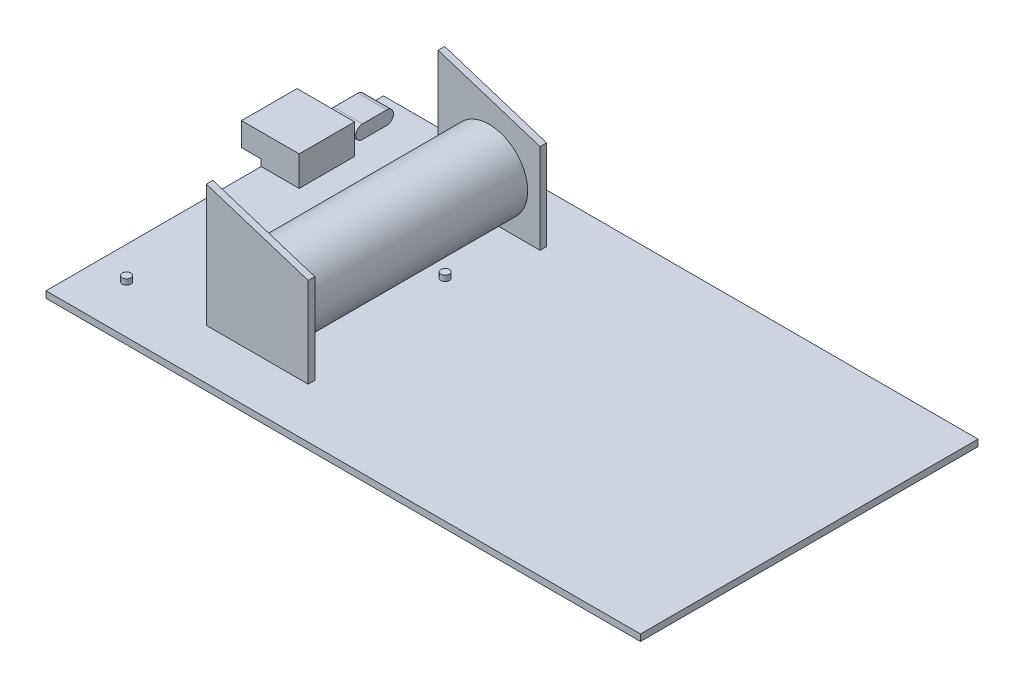
SolidWorks part; units mm, degrees
ref_plane "Front Plane" through (0, 0, 0) normal (0, 0, 1) x (1, 0, 0)
ref_plane "Top Plane" through (0, 0, 0) normal (0, 1, 0) x (1, 0, 0)
ref_plane "Right Plane" through (0, 0, 0) normal (1, 0, 0) x (0, 0, -1)
sketch "Sketch1" plane through (0, 0, 0) normal (0, 1, 0) x (1, 0, 0)
  line L1 (-70.45, -40) -> (70.45, -40)
  line L2 (-70.45, -40) -> (-70.45, 40)
  line L3 (-70.45, 40) -> (70.45, 40)
  line L4 (70.45, -40) -> (70.45, 40)
  line L5 (-70.45, -40) -> (70.45, 40) construction
  line L6 (-70.45, 40) -> (70.45, -40) construction
  point P0 (0, 0)
  dimension "D1" = 140.9
  dimension "D2" = 80
extrude "PCB" add sketch "Sketch1" along normal blind 1.55
sketch "Sketch2" plane through (-70.45, 0, 0) normal (-1, 0, 0) x (0, 0, 1)
  line L0 (-31.43, 1.55) -> (-31.43, 3.15)
  line L1 (-40, 1.55) -> (40, 1.55) construction
  line L2 (-40, 1.55) -> (-40, 0) construction
  dimension "D1" = 1.6
  dimension "D2" = 8.57
sketch "Sketch3" plane through (-70.45, 0, 0) normal (-1, 0, 0) x (0, 0, 1)
  line L0 (-34.3, 3.15) -> (-28.56, 3.15) construction
  line L1 (-34.3, 4.75) -> (-28.56, 4.75)
  line L2 (-34.3, 1.55) -> (-28.56, 1.55)
  arc A0 (-34.3, 4.75) -> (-34.3, 1.55) centre (-34.3, 3.15) ccw
  arc A1 (-28.56, 1.55) -> (-28.56, 4.75) centre (-28.56, 3.15) ccw
  point P2 (-31.43, 3.15)
  dimension "D1" = 5.74
extrude "bodyC" add sketch "Sketch3" against normal blind 6.45 and the other way blind 0.4
sketch "Sketch4" plane through (0, 1.55, 0) normal (0, 1, 0) x (1, 0, 0)
  line L0 (70.45, 40) -> (-70.45, 40) construction
  line L1 (-61.45, 11) -> (-75.1, 11)
  line L2 (-61.45, 11) -> (-61.45, 24.15)
  line L3 (-61.45, 24.15) -> (-75.1, 24.15)
  line L4 (-75.1, 11) -> (-75.1, 24.15)
  line L6 (-70.45, 28.56) -> (-70.45, -40) construction
  dimension "D1" = 13.65
  dimension "D2" = 13.15
  dimension "D3" = 15.85
  dimension "D4" = 4.65
extrude "Boss-Extrude4" add sketch "Sketch4" along normal blind 7.1 and the other way blind 1.55
sketch "Sketch5" plane through (0, 0, -11) normal (0, 0, 1) x (1, 0, 0)
  line L0 (-75.1, 0) -> (-75.1, 8.65) construction
  line L1 (-70.45, 0) -> (-75.1, 0)
  line L2 (-70.45, 0) -> (-70.45, 3.1)
  line L3 (-70.45, 3.1) -> (-75.1, 3.1)
  line L4 (-75.1, 0) -> (-75.1, 3.1)
  dimension "D1" = 3.1
extrude "Cut-Extrude3" cut sketch "Sketch5" against normal blind 14.1
sketch "Sketch11" plane through (0, 1.55, 0) normal (0, 1, 0) x (1, 0, 0)
  line L1 (-44.35, 26.85) -> (-20.2, 26.85)
  line L2 (-44.35, 26.85) -> (-44.35, 28.4)
  line L3 (-44.35, 28.4) -> (-20.2, 28.4)
  line L4 (-20.2, 26.85) -> (-20.2, 28.4)
  line L6 (70.45, 40) -> (-70.45, 40) construction
  line L7 (-70.45, 40) -> (-70.45, 34.3) construction
  dimension "D1" = 11.6
  dimension "D2" = 26.1
  dimension "D3" = 1.55
  dimension "D4" = 24.15
extrude "Boss-Extrude8" add sketch "Sketch11" along normal blind 29
sketch "Sketch7" plane through (0, 1.55, 0) normal (0, 1, 0) x (1, 0, 0)
  line L0 (-70.45, 11) -> (-70.45, -40) construction
  line L1 (-44.35, -28.1) -> (-20.2, -28.1)
  line L2 (-44.35, -28.1) -> (-44.35, -26.55)
  line L3 (-44.35, -26.55) -> (-20.2, -26.55)
  line L4 (-20.2, -28.1) -> (-20.2, -26.55)
  line L5 (-70.45, -40) -> (70.45, -40) construction
  dimension "D1" = 26.1
  dimension "D2" = 11.9
  dimension "D3" = 1.55
  dimension "D4" = 24.15
extrude "Boss-Extrude5" add sketch "Sketch7" along normal blind 29
sketch "Sketch8" plane through (0, 0, 28.1) normal (0, 0, 1) x (1, 0, 0)
  line L0 (-44.35, 30.55) -> (-20.2, 22.85)
  line L1 (-20.2, 30.55) -> (-20.2, 1.55) construction
  line L5 (-20.2, 30.55) -> (-44.35, 30.55)
  line L6 (-20.2, 22.85) -> (-20.2, 30.55)
extrude "Cut-Extrude4" cut sketch "Sketch8" against normal blind 89
sketch "Sketch12" plane through (0, 0, -26.85) normal (0, 0, 1) x (1, 0, 0)
  line L0 (-32.275, 1.55) -> (-32.275, 12.25)
  line L1 (-44.35, 1.55) -> (-20.2, 1.55) construction
  circle A0 centre (-32.275, 12.25) radius 9.15
  dimension "D1" = 10.7
extrude "Battery" add sketch "Sketch12" along normal blind 54
sketch "Sketch13" plane through (0, 1.55, 0) normal (0, 1, 0) x (1, 0, 0)
  line L0 (-70.45, -28.6) -> (-62.75, -28.6)
  line L1 (-70.45, 11) -> (-70.45, -40) construction
  line L2 (-70.45, -40) -> (70.45, -40) construction
  circle A0 centre (-62.75, -28.6) radius 1
  dimension "D1" = 7.7
  dimension "D2" = 11.4
extrude "Button" add sketch "Sketch13" along normal blind 1.3 contours A0
sketch "Sketch14" plane through (0, 1.55, 0) normal (0, 1, 0) x (1, 0, 0)
  line L0 (-33.45, 9.9) -> (-25.75, 9.9)
  line L3 (70.45, 40) -> (-70.45, 40) construction
  line L4 (70.45, -40) -> (70.45, 40) construction
  circle A0 centre (-25.75, 9.9) radius 1
  dimension "D3" = 96.2
  dimension "D2" = 30.1
  dimension "D1" = 7.7
extrude "Reset" add sketch "Sketch14" along normal blind 1.3 contours A0
